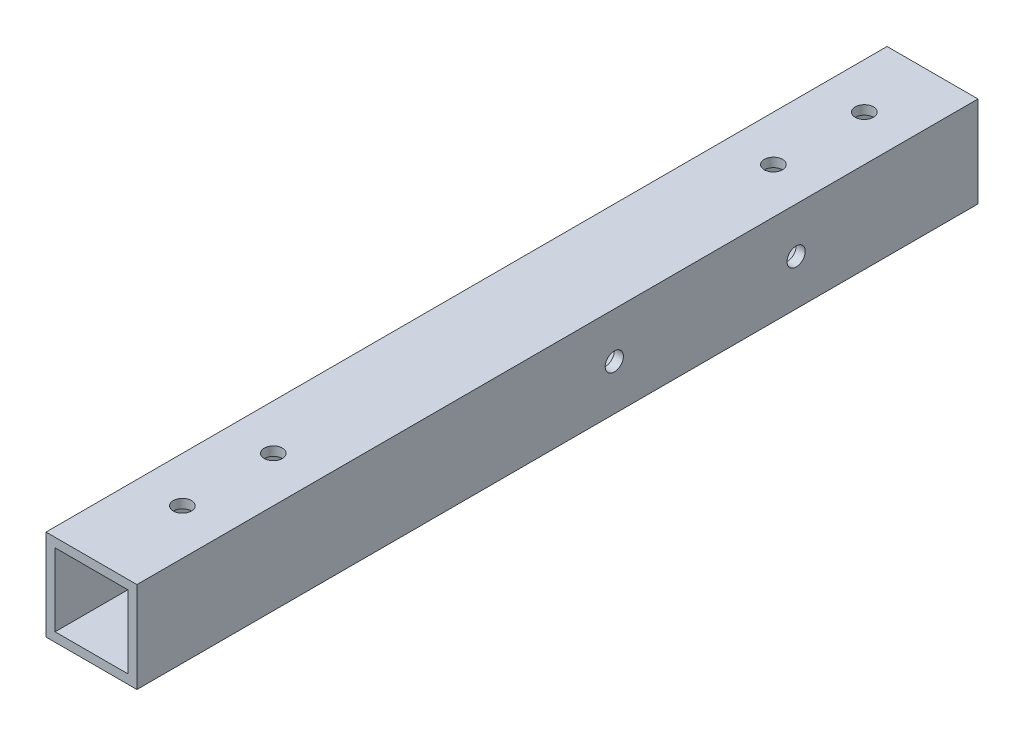
SolidWorks part; units mm, degrees
ref_plane "前视基准面" through (0, 0, 0) normal (0, 0, 1) x (1, 0, 0)
ref_plane "上视基准面" through (0, 0, 0) normal (0, 1, 0) x (1, 0, 0)
ref_plane "右视基准面" through (0, 0, 0) normal (1, 0, 0) x (0, 0, -1)
sketch "草图1" plane through (0, 0, 0) normal (0, 0, 1) x (1, 0, 0)
  line L1 (-10, -10) -> (10, -10)
  line L2 (-10, -10) -> (-10, 10)
  line L3 (-10, 10) -> (10, 10)
  line L4 (10, -10) -> (10, 10)
  line L5 (-10, -10) -> (10, 10) construction
  line L6 (-10, 10) -> (10, -10) construction
  line L7 (-8, 8) -> (8, 8)
  line L8 (-8, 8) -> (-8, -8)
  line L9 (-8, -8) -> (8, -8)
  line L10 (8, 8) -> (8, -8)
  line L11 (-8, 8) -> (8, -8) construction
  line L12 (-8, -8) -> (8, 8) construction
  point P0 (0, 0)
  point P5 (0, 0)
  dimension "D1" = 20
  dimension "D2" = 16
extrude "凸台-拉伸1" add sketch "草图1" along normal blind 185
sketch "草图2" plane through (0, 10, 0) normal (0, 1, 0) x (1, 0, 0)
  line L0 (0, -1000) -> (0, 49000) construction
  line L1 (10, 0) -> (-10, 0) construction
  line L2 (10, -185) -> (-10, -185) construction
  circle A0 centre (0, -15) radius 2
  circle A1 centre (0, -35) radius 2
  circle A2 centre (0, -165) radius 2
  circle A3 centre (0, -145) radius 2
  dimension "D1" = 4
  dimension "D2" = 4
  dimension "D3" = 4
  dimension "D4" = 4
  dimension "D5" = 15
  dimension "D6" = 20
  dimension "D7" = 20
  dimension "D8" = 20
extrude "切除-拉伸1" cut sketch "草图2" against normal through all
sketch "草图3" plane through (-10, 0, 0) normal (-1, 0, 0) x (0, 0, 1)
  line L0 (-1000, 0) -> (49000, 0) construction
  line L1 (0, 10) -> (0, -10) construction
  circle A1 centre (40, 0) radius 2
  circle A2 centre (80, 0) radius 2
  point P7 (0, 0)
  dimension "D1" = 4
  dimension "D2" = 4
  dimension "D3" = 40
  dimension "D4" = 40
extrude "切除-拉伸2" cut sketch "草图3" against normal through all
